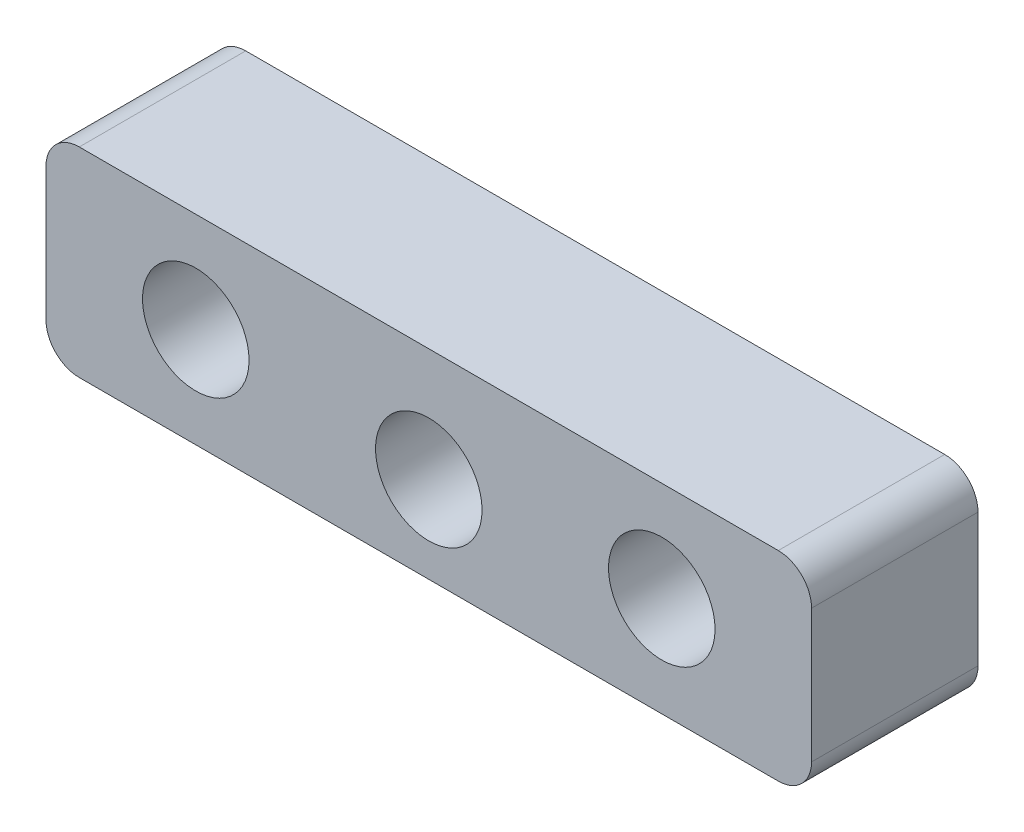
SolidWorks part; units mm, degrees
material "A-玻璃纤维"
ref_plane "前视基准面" through (0, 0, 0) normal (0, 0, 1) x (1, 0, 0)
ref_plane "上视基准面" through (0, 0, 0) normal (0, 1, 0) x (1, 0, 0)
ref_plane "右视基准面" through (0, 0, 0) normal (1, 0, 0) x (0, 0, -1)
other "Configuration Table"
sketch "草图1" plane through (0, 0, 0) normal (0, 0, 1) x (1, 0, 0)
  line L1 (-11.5, 3) -> (11.5, 3)
  line L2 (-11.5, 3) -> (-11.5, -3)
  line L3 (-11.5, -3) -> (11.5, -3)
  line L4 (11.5, 3) -> (11.5, -3)
  line L5 (-11.5, 3) -> (11.5, -3) construction
  line L6 (-11.5, -3) -> (11.5, 3) construction
  point P0 (0, 0)
  dimension "D1" = 6
  dimension "D2" = 23
extrude "凸台-拉伸1" add sketch "草图1" along normal blind 5
sketch "草图2" plane through (0, 0, 5) normal (0, 0, 1) x (1, 0, 0)
  line L0 (-11.5, 0) -> (11.5, 0) construction
  line L1 (-11.5, 3) -> (-11.5, -3) construction
  line L2 (11.5, -3) -> (11.5, 3) construction
  line L3 (0, 3) -> (0, -3) construction
  line L4 (11.5, 3) -> (-11.5, 3) construction
  line L5 (-11.5, -3) -> (11.5, -3) construction
  circle A0 centre (-7, 0) radius 1.6
  circle A1 centre (7, 0) radius 1.6
  circle A2 centre (0, -0.4) radius 1.6
  dimension "D1" = 3.2
  dimension "D2" = 3.2
  dimension "D3" = 7
  dimension "D5" = 3.2
  dimension "D4" = 14
  dimension "D6" = 0.4
extrude "切除-拉伸1" cut sketch "草图2" against normal blind 5
fillet "圆角1" radius 1 4 edges at (11.5, -3, 2.5) (11.5, 3, 2.5) (-11.5, 3, 2.5) (-11.5, -3, 2.5)
